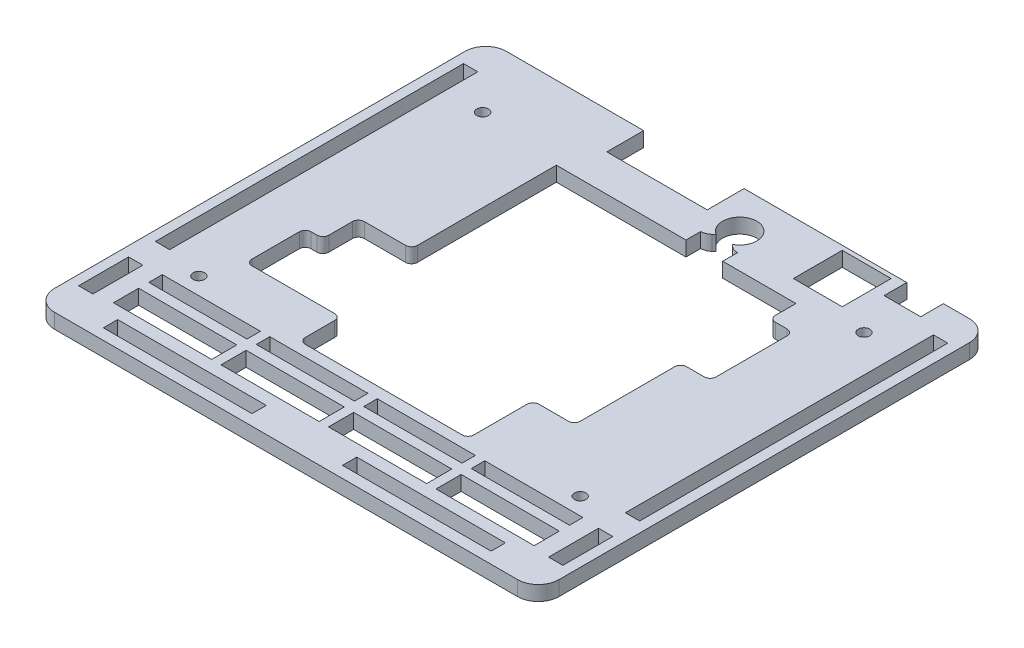
SolidWorks part; units mm, degrees
ref_plane "Front Plane" through (0, 0, 0) normal (0, 0, 1) x (1, 0, 0)
ref_plane "Top Plane" through (0, 0, 0) normal (0, 1, 0) x (1, 0, 0)
ref_plane "Right Plane" through (0, 0, 0) normal (1, 0, 0) x (0, 0, -1)
sketch "Sketch1" plane through (0, 0, 0) normal (0, 1, 0) x (1, 0, 0)
  line L0 (-20.2692, 48.5775) -> (-20.2692, 40.6527)
  line L1 (-54.229, 48.5775) -> (-20.2692, 48.5775)
  line L2 (-54.229, 48.5775) -> (-54.229, -48.5775)
  line L3 (-54.229, -48.5775) -> (54.229, -48.5775)
  line L4 (54.229, 48.5775) -> (54.229, -48.5775)
  line L5 (-20.2692, 40.6527) -> (1.3208, 40.6527)
  line L6 (1.3208, 40.6527) -> (1.3208, 48.5775)
  line L7 (36.2966, 48.5775) -> (36.2966, 43.0657)
  line L8 (36.2966, 43.0657) -> (37.1348, 43.0657)
  line L9 (37.1348, 43.0657) -> (37.1348, 38.7223)
  line L10 (37.1348, 38.7223) -> (47.1424, 38.7223)
  line L11 (47.1424, 38.7223) -> (47.1424, 42.7014)
  line L12 (47.1424, 42.7014) -> (44.1706, 42.7014)
  line L13 (44.1706, 42.7014) -> (44.1706, 48.5775)
  line L14 (1.3208, 48.5775) -> (36.2966, 48.5775)
  line L15 (44.1706, 48.5775) -> (54.229, 48.5775)
  dimension "D1" = 108.458
  dimension "D2" = 97.155
  dimension "D3" = 54.229
  dimension "D4" = 48.5775
  dimension "D5" = 7.9248
  dimension "D6" = 21.59
  dimension "D7" = 33.9598
  dimension "D8" = 0.8382
  dimension "D9" = 5.5118
  dimension "D10" = 4.3434
  dimension "D11" = 7.874
  dimension "D12" = 10.0076
  dimension "D13" = 10.0584
extrude "Boss-Extrude1" add sketch "Sketch1" along normal mid plane 3.175
sketch "Sketch2" plane through (0, 1.5875, 0) normal (0, 1, 0) x (1, 0, 0)
  line L0 (-1000, 0) -> (49000, 0) construction
  line L1 (0, -1000) -> (0, 49000) construction
  line L2 (-40.9956, -1044.838) -> (-40.9956, 48955.162) construction
  line L3 (-54.229, 48.5775) -> (-54.229, -48.5775) construction
  line L4 (-20.2692, 48.5775) -> (-54.229, 48.5775) construction
  line L5 (-54.229, -48.5775) -> (54.229, -48.5775) construction
  circle A0 centre (-40.9956, 34.6837) radius 1.2446
  circle A1 centre (-40.9956, -26.3271) radius 1.2446
  circle A2 centre (40.9956, -26.3271) radius 1.2446
  circle A3 centre (40.9956, 34.6837) radius 1.2446
  dimension "D1" = 2.4892
  dimension "D2" = 2.4892
  dimension "D4" = 13.8938
  dimension "D5" = 22.2504
  dimension "D3" = 13.2334
extrude "Cut-Extrude1" cut sketch "Sketch2" against normal through all
sketch "Sketch3" plane through (0, 1.5875, 0) normal (0, 1, 0) x (1, 0, 0)
  line L0 (36.2966, 48.5775) -> (1.3208, 48.5775) construction
  line L1 (1.3208, 48.5775) -> (1.3208, 40.6527) construction
  line L2 (-21.9456, 35.9283) -> (4.6502, 35.9283)
  line L3 (28.2956, 34.6583) -> (28.2956, 28.3337)
  line L4 (29.5656, 27.0637) -> (32.1056, 27.0637)
  line L5 (33.3756, 25.7937) -> (33.3756, 10.5029)
  line L6 (32.1056, 9.2329) -> (28.2956, 9.2329)
  line L7 (27.0256, 7.9629) -> (27.0256, -12.3571)
  line L8 (25.7556, -13.6271) -> (19.4056, -13.6271)
  line L9 (18.1356, -14.8971) -> (18.1356, -26.3271)
  line L10 (16.8656, -27.5971) -> (-16.8656, -27.5971)
  line L11 (-18.1356, -26.3271) -> (-18.1356, -19.9771)
  line L12 (-19.4056, -18.7071) -> (-37.1856, -18.7071)
  line L13 (-38.4556, -17.4371) -> (-38.4556, -7.2771)
  line L14 (-37.1856, -6.0071) -> (-35.9156, -6.0071)
  line L15 (-34.6456, -4.7371) -> (-34.6456, 0.3429)
  line L16 (-33.3756, 1.6129) -> (-24.4856, 1.6129)
  line L17 (-23.2156, 2.8829) -> (-23.2156, 34.6583)
  line L18 (-54.229, 48.5775) -> (-54.229, -48.5775) construction
  line L19 (1.3208, 40.6527) -> (-20.2692, 40.6527) construction
  line L20 (12.5476, 35.9283) -> (27.0256, 35.9283)
  line L21 (6.4114, 36.6381) -> (6.8425, 37.0529)
  line L22 (10.7864, 36.6381) -> (10.4771, 36.9357)
  arc A0 (10.4771, 36.9357) -> (6.8425, 37.0529) centre (8.763, 40.1955) ccw
  arc A1 (-21.5117, 35.8519) -> (-23.2156, 34.6583) centre (-21.9456, 34.6583) ccw
  arc A2 (-21.9456, 35.9283) -> (-23.2156, 34.6583) centre (-21.9456, 34.6583) ccw
  arc A3 (-23.2156, 2.8829) -> (-24.4856, 1.6129) centre (-24.4856, 2.8829) cw
  arc A4 (-33.3756, 1.6129) -> (-34.6456, 0.3429) centre (-33.3756, 0.3429) ccw
  arc A5 (-34.6456, -4.7371) -> (-35.9156, -6.0071) centre (-35.9156, -4.7371) cw
  arc A6 (-37.1856, -6.0071) -> (-38.4556, -7.2771) centre (-37.1856, -7.2771) ccw
  arc A7 (-38.4556, -17.4371) -> (-37.1856, -18.7071) centre (-37.1856, -17.4371) ccw
  arc A8 (-19.4056, -18.7071) -> (-18.1356, -19.9771) centre (-19.4056, -19.9771) cw
  arc A9 (-18.1356, -26.3271) -> (-16.8656, -27.5971) centre (-16.8656, -26.3271) ccw
  arc A10 (16.8656, -27.5971) -> (18.1356, -26.3271) centre (16.8656, -26.3271) ccw
  arc A11 (18.1356, -14.8971) -> (19.4056, -13.6271) centre (19.4056, -14.8971) cw
  arc A12 (25.7556, -13.6271) -> (27.0256, -12.3571) centre (25.7556, -12.3571) ccw
  arc A13 (27.0256, 7.9629) -> (28.2956, 9.2329) centre (28.2956, 7.9629) cw
  arc A14 (32.1056, 9.2329) -> (33.3756, 10.5029) centre (32.1056, 10.5029) ccw
  arc A15 (33.3756, 25.7937) -> (32.1056, 27.0637) centre (32.1056, 25.7937) ccw
  arc A16 (29.5656, 27.0637) -> (28.2956, 28.3337) centre (29.5656, 28.3337) cw
  arc A17 (28.2956, 34.6583) -> (27.0256, 35.9283) centre (27.0256, 34.6583) ccw
  arc A18 (12.5476, 35.9283) -> (10.7864, 36.6381) centre (12.5476, 38.4683) cw
  arc A19 (4.6502, 35.9283) -> (6.4114, 36.6381) centre (4.6502, 38.4683) ccw
  point P34 (-23.2156, 1.6129)
  point P37 (-34.6456, 1.6129)
  point P40 (-34.6456, -6.0071)
  point P43 (-38.4556, -6.0071)
  point P46 (-38.4556, -18.7071)
  point P49 (-18.1356, -18.7071)
  point P52 (-18.1356, -27.5971)
  point P55 (18.1356, -27.5971)
  point P58 (18.1356, -13.6271)
  point P61 (27.0256, -13.6271)
  point P64 (27.0256, 9.2329)
  point P67 (33.3756, 9.2329)
  point P70 (33.3756, 27.0637)
  point P73 (28.2956, 27.0637)
  point P76 (28.2956, 35.9283)
  dimension "D1" = 7.366
  dimension "D2" = 8.382
  dimension "D3" = 7.4422
  dimension "D20" = 1.27
  dimension "D21" = 1.27
  dimension "D22" = 2.54
  dimension "D4" = 8.8646
  dimension "D5" = 5.08
  dimension "D6" = 17.8308
  dimension "D7" = 22.86
  dimension "D8" = 8.89
  dimension "D9" = 6.35
  dimension "D10" = 13.97
  dimension "D11" = 8.89
  dimension "D12" = 36.2712
  dimension "D13" = 20.32
  dimension "D14" = 12.7
  dimension "D15" = 3.81
  dimension "D16" = 7.62
  dimension "D17" = 11.43
  dimension "D18" = 31.0134
  dimension "D19" = 4.7244
  dimension "D23" = 15.748
  dimension "D24" = 26.162
extrude "Cut-Extrude2" cut sketch "Sketch3" against normal blind 3.175 contours A0 L21 L2 A1 L17 A3 L16 A4 L15 A5 L14 A6 L13 A7 L12 A8 L11 A9 L10 A10 L9 A11 L8 A12 L7 A13 L6 A14 L5 A15 L4 A16 L3 A17 L20 L22
sketch "Sketch4" plane through (0, 1.5875, 0) normal (0, 1, 0) x (1, 0, 0)
  line L0 (36.2966, 48.5775) -> (1.3208, 48.5775) construction
  line L1 (23.368, 47.6377) -> (33.8836, 47.6377)
  line L2 (23.368, 47.6377) -> (23.368, 37.1221)
  line L3 (23.368, 37.1221) -> (33.8836, 37.1221)
  line L4 (33.8836, 47.6377) -> (33.8836, 37.1221)
  line L5 (36.2966, 43.0657) -> (36.2966, 48.5775) construction
  line L6 (54.229, -48.5775) -> (54.229, 48.5775) construction
  line L7 (49.0474, 41.5671) -> (51.8668, 41.5671) construction
  line L8 (49.0474, 41.5671) -> (49.0474, -24.4221) construction
  line L9 (49.0474, -24.4221) -> (51.8668, -24.4221) construction
  line L10 (51.8668, 41.5671) -> (51.8668, -24.4221) construction
  line L11 (49.0474, -30.4419) -> (51.8668, -30.4419) construction
  line L12 (49.0474, -30.4419) -> (49.0474, -40.9321) construction
  line L13 (49.0474, -40.9321) -> (51.8668, -40.9321) construction
  line L14 (51.8668, -30.4419) -> (51.8668, -40.9321) construction
  line L15 (-54.229, -48.5775) -> (54.229, -48.5775) construction
  line L16 (54.229, 48.5775) -> (44.1706, 48.5775) construction
  line L17 (0, -1000) -> (0, 49000) construction
  line L18 (-51.9938, 41.5671) -> (-51.9938, -24.4221) construction
  line L19 (-51.9938, 41.5671) -> (-49.1744, 41.5671) construction
  line L20 (-49.1744, 41.5671) -> (-49.1744, -24.4221) construction
  line L21 (-51.9938, -24.4221) -> (-49.1744, -24.4221) construction
  line L22 (-51.9938, -30.4419) -> (-49.1744, -30.4419) construction
  line L23 (-51.9938, -30.4419) -> (-51.9938, -40.9321) construction
  line L24 (-49.1744, -30.4419) -> (-49.1744, -40.9321) construction
  line L25 (-51.9938, -40.9321) -> (-49.1744, -40.9321) construction
  line L26 (-52.1208, 41.6941) -> (-52.1208, -24.5491)
  line L27 (-52.1208, -24.5491) -> (-49.0474, -24.5491)
  line L28 (-49.0474, 41.6941) -> (-49.0474, -24.5491)
  line L29 (-52.1208, 41.6941) -> (-49.0474, 41.6941)
  line L30 (-52.1208, -30.3149) -> (-49.0474, -30.3149)
  line L31 (-49.0474, -30.3149) -> (-49.0474, -41.0591)
  line L32 (-52.1208, -41.0591) -> (-49.0474, -41.0591)
  line L33 (-52.1208, -30.3149) -> (-52.1208, -41.0591)
  line L34 (48.9204, 41.6941) -> (51.9938, 41.6941)
  line L35 (51.9938, 41.6941) -> (51.9938, -24.5491)
  line L36 (48.9204, -24.5491) -> (51.9938, -24.5491)
  line L37 (48.9204, 41.6941) -> (48.9204, -24.5491)
  line L38 (48.9204, -30.3149) -> (51.9938, -30.3149)
  line L39 (51.9938, -30.3149) -> (51.9938, -41.0591)
  line L40 (48.9204, -41.0591) -> (51.9938, -41.0591)
  line L41 (48.9204, -30.3149) -> (48.9204, -41.0591)
  dimension "D1" = 10.5156
  dimension "D2" = 10.5156
  dimension "D3" = 0.9398
  dimension "D4" = 2.413
  dimension "D5" = 2.8194
  dimension "D6" = 2.8194
  dimension "D7" = 2.3622
  dimension "D8" = 2.3622
  dimension "D9" = 7.6454
  dimension "D10" = 10.4902
  dimension "D11" = 65.9892
  dimension "D12" = 7.0104
  dimension "D14" = 0.127
  dimension "D13" = 2
extrude "Cut-Extrude3" cut sketch "Sketch4" against normal blind 3.175
sketch "Sketch5" plane through (0, 1.5875, 0) normal (0, 1, 0) x (1, 0, 0)
  line L0 (-54.229, -48.5775) -> (54.229, -48.5775) construction
  line L1 (-45.212, -29.9847) -> (-24.1046, -29.9847) construction
  line L2 (-45.212, -29.9847) -> (-45.212, -32.8803) construction
  line L3 (-45.212, -32.8803) -> (-24.1046, -32.8803) construction
  line L4 (-24.1046, -29.9847) -> (-24.1046, -32.8803) construction
  line L5 (-45.212, -35.0647) -> (-24.1046, -35.0647) construction
  line L6 (-45.212, -35.0647) -> (-45.212, -40.4749) construction
  line L7 (-45.212, -40.4749) -> (-24.1046, -40.4749) construction
  line L8 (-24.1046, -35.0647) -> (-24.1046, -40.4749) construction
  line L9 (-54.229, 48.5775) -> (-54.229, -48.5775) construction
  line L10 (-22.098, -29.9847) -> (-22.098, -32.8803) construction
  line L11 (-22.098, -29.9847) -> (-0.9906, -29.9847) construction
  line L12 (-0.9906, -29.9847) -> (-0.9906, -32.8803) construction
  line L13 (-22.098, -32.8803) -> (-0.9906, -32.8803) construction
  line L14 (-22.098, -35.0647) -> (-22.098, -40.4749) construction
  line L15 (-22.098, -35.0647) -> (-0.9906, -35.0647) construction
  line L16 (-0.9906, -35.0647) -> (-0.9906, -40.4749) construction
  line L17 (-22.098, -40.4749) -> (-0.9906, -40.4749) construction
  line L18 (1.016, -29.9847) -> (1.016, -32.8803) construction
  line L19 (1.016, -29.9847) -> (22.1234, -29.9847) construction
  line L20 (22.1234, -29.9847) -> (22.1234, -32.8803) construction
  line L21 (1.016, -32.8803) -> (22.1234, -32.8803) construction
  line L22 (1.016, -35.0647) -> (1.016, -40.4749) construction
  line L23 (1.016, -35.0647) -> (22.1234, -35.0647) construction
  line L24 (22.1234, -35.0647) -> (22.1234, -40.4749) construction
  line L25 (1.016, -40.4749) -> (22.1234, -40.4749) construction
  line L26 (24.13, -29.9847) -> (24.13, -32.8803) construction
  line L27 (24.13, -29.9847) -> (45.2374, -29.9847) construction
  line L28 (45.2374, -29.9847) -> (45.2374, -32.8803) construction
  line L29 (24.13, -32.8803) -> (45.2374, -32.8803) construction
  line L30 (24.13, -35.0647) -> (24.13, -40.4749) construction
  line L31 (24.13, -35.0647) -> (45.2374, -35.0647) construction
  line L32 (45.2374, -35.0647) -> (45.2374, -40.4749) construction
  line L33 (24.13, -40.4749) -> (45.2374, -40.4749) construction
  line L34 (-45.466, -29.7307) -> (-23.8506, -29.7307) construction
  line L35 (-23.8506, -29.7307) -> (-23.8506, -33.1343) construction
  line L36 (-45.466, -33.1343) -> (-23.8506, -33.1343) construction
  line L37 (-45.466, -29.7307) -> (-45.466, -33.1343) construction
  line L38 (-45.466, -34.8107) -> (-23.8506, -34.8107) construction
  line L39 (-23.8506, -34.8107) -> (-23.8506, -40.7289) construction
  line L40 (-45.466, -40.7289) -> (-23.8506, -40.7289) construction
  line L41 (-45.466, -34.8107) -> (-45.466, -40.7289) construction
  line L42 (-22.352, -29.7307) -> (-22.352, -33.1343) construction
  line L43 (-22.352, -33.1343) -> (-0.7366, -33.1343) construction
  line L44 (-0.7366, -29.7307) -> (-0.7366, -33.1343) construction
  line L45 (-22.352, -29.7307) -> (-0.7366, -29.7307) construction
  line L46 (-22.352, -34.8107) -> (-22.352, -40.7289) construction
  line L47 (-22.352, -40.7289) -> (-0.7366, -40.7289) construction
  line L48 (-0.7366, -34.8107) -> (-0.7366, -40.7289) construction
  line L49 (-22.352, -34.8107) -> (-0.7366, -34.8107) construction
  line L50 (0.762, -29.7307) -> (0.762, -33.1343) construction
  line L51 (0.762, -33.1343) -> (22.3774, -33.1343) construction
  line L52 (22.3774, -29.7307) -> (22.3774, -33.1343) construction
  line L53 (0.762, -29.7307) -> (22.3774, -29.7307) construction
  line L54 (0.762, -34.8107) -> (0.762, -40.7289) construction
  line L55 (0.762, -40.7289) -> (22.3774, -40.7289) construction
  line L56 (22.3774, -34.8107) -> (22.3774, -40.7289) construction
  line L57 (0.762, -34.8107) -> (22.3774, -34.8107) construction
  line L58 (23.876, -29.7307) -> (23.876, -33.1343) construction
  line L59 (23.876, -33.1343) -> (45.4914, -33.1343) construction
  line L60 (45.4914, -29.7307) -> (45.4914, -33.1343) construction
  line L61 (23.876, -29.7307) -> (45.4914, -29.7307) construction
  line L62 (23.876, -34.8107) -> (23.876, -40.7289) construction
  line L63 (23.876, -40.7289) -> (45.4914, -40.7289) construction
  line L64 (45.4914, -34.8107) -> (45.4914, -40.7289) construction
  line L65 (23.876, -34.8107) -> (45.4914, -34.8107) construction
  line L66 (-45.212, -29.9847) -> (-24.1046, -29.9847)
  line L67 (-24.1046, -29.9847) -> (-24.1046, -32.8803)
  line L68 (-45.212, -32.8803) -> (-24.1046, -32.8803)
  line L69 (-45.212, -29.9847) -> (-45.212, -32.8803)
  line L70 (-45.212, -35.0647) -> (-24.1046, -35.0647)
  line L71 (-24.1046, -35.0647) -> (-24.1046, -40.4749)
  line L72 (-45.212, -40.4749) -> (-24.1046, -40.4749)
  line L73 (-45.212, -35.0647) -> (-45.212, -40.4749)
  line L74 (-22.098, -35.0647) -> (-22.098, -40.4749)
  line L75 (-22.098, -40.4749) -> (-0.9906, -40.4749)
  line L76 (-0.9906, -35.0647) -> (-0.9906, -40.4749)
  line L77 (-22.098, -35.0647) -> (-0.9906, -35.0647)
  line L78 (-22.098, -32.8803) -> (-0.9906, -32.8803)
  line L79 (-0.9906, -29.9847) -> (-0.9906, -32.8803)
  line L80 (-22.098, -29.9847) -> (-0.9906, -29.9847)
  line L81 (-22.098, -29.9847) -> (-22.098, -32.8803)
  line L82 (1.016, -32.8803) -> (22.1234, -32.8803)
  line L83 (22.1234, -29.9847) -> (22.1234, -32.8803)
  line L84 (1.016, -29.9847) -> (22.1234, -29.9847)
  line L85 (1.016, -29.9847) -> (1.016, -32.8803)
  line L86 (1.016, -35.0647) -> (22.1234, -35.0647)
  line L87 (22.1234, -35.0647) -> (22.1234, -40.4749)
  line L88 (1.016, -40.4749) -> (22.1234, -40.4749)
  line L89 (1.016, -35.0647) -> (1.016, -40.4749)
  line L90 (24.13, -35.0647) -> (24.13, -40.4749)
  line L91 (24.13, -40.4749) -> (45.2374, -40.4749)
  line L92 (45.2374, -35.0647) -> (45.2374, -40.4749)
  line L93 (24.13, -35.0647) -> (45.2374, -35.0647)
  line L94 (24.13, -32.8803) -> (45.2374, -32.8803)
  line L95 (45.2374, -29.9847) -> (45.2374, -32.8803)
  line L96 (24.13, -29.9847) -> (45.2374, -29.9847)
  line L97 (24.13, -29.9847) -> (24.13, -32.8803)
  dimension "D1" = 21.1074
  dimension "D2" = 21.1074
  dimension "D3" = 2.8956
  dimension "D4" = 5.4102
  dimension "D5" = 2.1844
  dimension "D6" = 8.1026
  dimension "D7" = 9.017
  dimension "D8" = 9.017
  dimension "D10" = 0.254
  dimension "D11" = 0.254
  dimension "D9" = 4
extrude "Cut-Extrude4" cut sketch "Sketch5" against normal blind 3.175
sketch "Sketch7" plane through (0, 1.5875, 0) normal (0, 1, 0) x (1, 0, 0)
  line L0 (54.229, -48.5775) -> (54.229, 48.5775) construction
  line L1 (-41.5036, -43.2817) -> (-9.8044, -43.2817) construction
  line L2 (-41.5036, -43.2817) -> (-41.5036, -46.1011) construction
  line L3 (-41.5036, -46.1011) -> (-9.8044, -46.1011) construction
  line L4 (-9.8044, -43.2817) -> (-9.8044, -46.1011) construction
  line L5 (9.8044, -43.1813) -> (41.5036, -43.1813) construction
  line L6 (9.8044, -43.1813) -> (9.8044, -46.0007) construction
  line L7 (9.8044, -46.0007) -> (41.5036, -46.0007) construction
  line L8 (41.5036, -43.1813) -> (41.5036, -46.0007) construction
  line L9 (-54.229, 48.5775) -> (-54.229, -48.5775) construction
  line L10 (-41.6306, -43.1547) -> (-9.6774, -43.1547)
  line L11 (-9.6774, -43.1547) -> (-9.6774, -46.2281)
  line L12 (-41.6306, -46.2281) -> (-9.6774, -46.2281)
  line L13 (-41.6306, -43.1547) -> (-41.6306, -46.2281)
  line L14 (9.6774, -43.0543) -> (41.6306, -43.0543)
  line L15 (41.6306, -43.0543) -> (41.6306, -46.1277)
  line L16 (9.6774, -46.1277) -> (41.6306, -46.1277)
  line L17 (9.6774, -43.0543) -> (9.6774, -46.1277)
  dimension "D1" = 31.6992
  dimension "D2" = 31.6992
  dimension "D3" = 2.8194
  dimension "D4" = 2.8194
  dimension "D5" = 12.7254
  dimension "D6" = 12.7254
  dimension "D7" = 0.127
extrude "Cut-Extrude5" cut sketch "Sketch7" against normal blind 3.175
fillet "Fillet1" radius 4.445 4 edges at (-54.229, 0, -48.5775) (54.229, 0, -48.5775) (54.229, 0, 48.5775) (-54.229, 0, 48.5775)
sketch "Sketch8" plane through (0, 1.5875, 0) normal (0, 1, 0) x (1, 0, 0)
  line L0 (36.2966, 43.0657) -> (36.2966, 48.5775) construction
  line L2 (37.1348, 43.0657) -> (37.1348, 38.7223)
  line L3 (37.1348, 38.7223) -> (47.1424, 38.7223)
  line L4 (47.1424, 43.0657) -> (47.1424, 38.7223)
  line L5 (36.2966, 43.7007) -> (47.1424, 43.7007)
  line L6 (36.2966, 43.7007) -> (36.2966, 43.0657)
  line L7 (36.2966, 43.0657) -> (37.1348, 43.0657)
  line L8 (47.1424, 43.7007) -> (47.1424, 43.0657)
  dimension "D1" = 0.635
extrude "Boss-Extrude2" add sketch "Sketch8" against normal up to surface (3.175 mm away) up to face at (25.654, -1.5875, 44.591)
sketch "Sketch9" plane through (0, 1.5875, 0) normal (0, 1, 0) x (1, 0, 0)
  line L0 (28.2956, 34.6583) -> (28.2956, 28.3337) construction
  line L1 (-21.9456, 35.9283) -> (4.6502, 35.9283) construction
  line L2 (-23.2156, 34.6583) -> (-23.2156, 35.9283)
  line L3 (-23.2156, 35.9283) -> (4.6502, 35.9283)
  line L4 (28.2956, 34.6583) -> (28.2956, 35.9283)
  line L5 (4.6502, 35.9283) -> (4.6502, 32.7533)
  line L6 (-23.2156, 34.6583) -> (-23.2156, 32.7533)
  line L7 (-23.2156, 32.7533) -> (4.6502, 32.7533)
  line L8 (28.2956, 34.6583) -> (28.2956, 32.7533)
  line L9 (12.5476, 35.9283) -> (12.5476, 32.7533)
  line L10 (12.5476, 35.9283) -> (28.2956, 35.9283)
  line L11 (12.5476, 32.7533) -> (28.2956, 32.7533)
  dimension "D1" = 3.175
extrude "Boss-Extrude3" add sketch "Sketch9" against normal up to surface (3.175 mm away)
equation "\"D3@Sketch1\"=.5*\"D1@Sketch1\""
equation "\"D4@Sketch1\"=.5*\"D2@Sketch1\""
